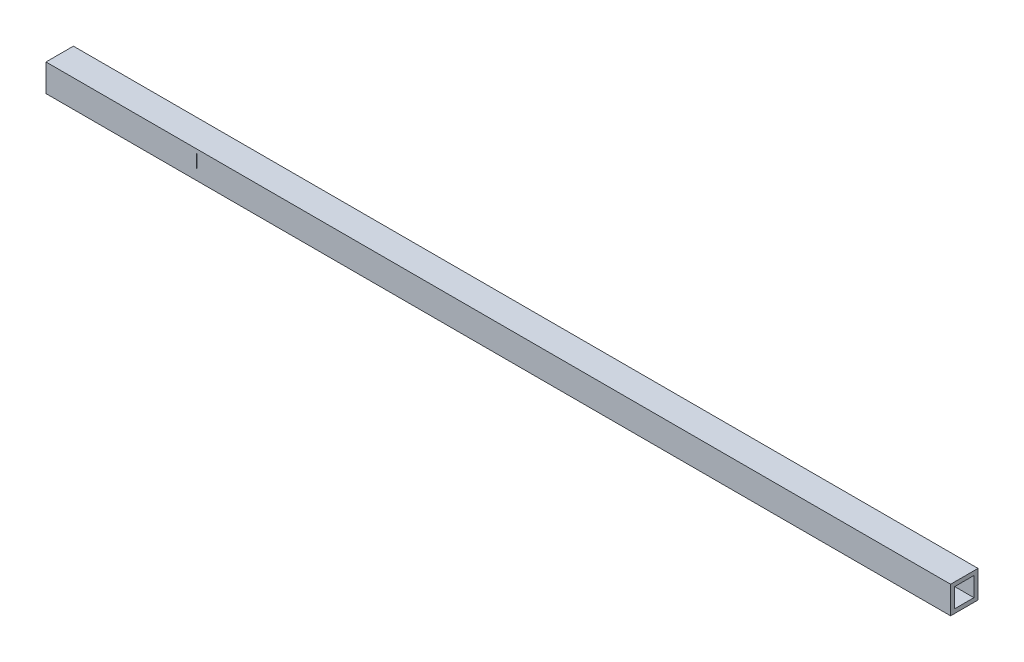
SolidWorks part; units mm, degrees
ref_plane "Alzado" through (0, 0, 0) normal (0, 0, 1) x (1, 0, 0)
ref_plane "Planta" through (0, 0, 0) normal (0, 1, 0) x (1, 0, 0)
ref_plane "Vista lateral" through (0, 0, 0) normal (1, 0, 0) x (0, 0, -1)
ref_plane "Plano1" through (0, -5, 0) normal (0, -1, 0) x (1, 0, 0)
sketch "Croquis1" plane through (0, -5, 0) normal (0, -1, 0) x (1, 0, 0)
  line L0 (0, 5) -> (0, -5)
  line L1 (0, -5) -> (330, -5)
  line L2 (330, -5) -> (330, 5)
  line L3 (330, 5) -> (0, 5)
  dimension "D1" = 330
extrude "Saliente-Extruir1" add sketch "Croquis1" against normal blind 10
sketch "Croquis2" plane through (0, 0, 0) normal (-1, 0, 0) x (0, 0, 1)
  line L0 (3.5, 3.5) -> (-3.5, 3.5)
  line L1 (-3.5, 3.5) -> (-3.5, -3.5)
  line L2 (-3.5, -3.5) -> (3.5, -3.5)
  line L3 (3.5, -3.5) -> (3.5, 3.5)
extrude "Cortar-Extruir1" cut sketch "Croquis2" against normal through all
sketch "Croquis3" plane through (0, 0, 5) normal (0, 0, 1) x (1, 0, 0)
  line L0 (25.01, -1.1667) -> (25.01, 3.5)
  line L1 (25.01, 3.5) -> (24.99, 3.5)
  line L2 (24.99, 3.5) -> (24.99, -1.1667)
  line L3 (24.99, -1.1667) -> (25.01, -1.1667)
extrude "Cortar-Extruir2" cut sketch "Croquis3" against normal blind 0.02
sketch "Croquis4" plane through (0, 0, 5) normal (0, 0, 1) x (1, 0, 0)
  line L0 (35.01, -1.1667) -> (35.01, 3.5)
  line L1 (35.01, 3.5) -> (34.99, 3.5)
  line L2 (34.99, 3.5) -> (34.99, -1.1667)
  line L3 (34.99, -1.1667) -> (35.01, -1.1667)
extrude "Cortar-Extruir3" cut sketch "Croquis4" against normal blind 0.02
sketch "Croquis5" plane through (0, 0, 5) normal (0, 0, 1) x (1, 0, 0)
  line L0 (45.01, -1.1667) -> (45.01, 3.5)
  line L1 (45.01, 3.5) -> (44.99, 3.5)
  line L2 (44.99, 3.5) -> (44.99, -1.1667)
  line L3 (44.99, -1.1667) -> (45.01, -1.1667)
extrude "Cortar-Extruir4" cut sketch "Croquis5" against normal blind 0.02
sketch "Croquis6" plane through (0, 0, 5) normal (0, 0, 1) x (1, 0, 0)
  line L0 (55.01, -1.1667) -> (55.01, 3.5)
  line L1 (55.01, 3.5) -> (54.99, 3.5)
  line L2 (54.99, 3.5) -> (54.99, -1.1667)
  line L3 (54.99, -1.1667) -> (55.01, -1.1667)
extrude "Cortar-Extruir5" cut sketch "Croquis6" against normal blind 0.02
sketch "Croquis7" plane through (0, 0, 5) normal (0, 0, 1) x (1, 0, 0)
  line L0 (65.01, -1.1667) -> (65.01, 3.5)
  line L1 (65.01, 3.5) -> (64.99, 3.5)
  line L2 (64.99, 3.5) -> (64.99, -1.1667)
  line L3 (64.99, -1.1667) -> (65.01, -1.1667)
extrude "Cortar-Extruir6" cut sketch "Croquis7" against normal blind 0.02
sketch "Croquis8" plane through (0, 0, 5) normal (0, 0, 1) x (1, 0, 0)
  line L0 (75.01, -1.1667) -> (75.01, 3.5)
  line L1 (75.01, 3.5) -> (74.99, 3.5)
  line L2 (74.99, 3.5) -> (74.99, -1.1667)
  line L3 (74.99, -1.1667) -> (75.01, -1.1667)
extrude "Cortar-Extruir7" cut sketch "Croquis8" against normal blind 0.02
sketch "Croquis9" plane through (0, 0, 5) normal (0, 0, 1) x (1, 0, 0)
  line L0 (85.01, -1.1667) -> (85.01, 3.5)
  line L1 (85.01, 3.5) -> (84.99, 3.5)
  line L2 (84.99, 3.5) -> (84.99, -1.1667)
  line L3 (84.99, -1.1667) -> (85.01, -1.1667)
extrude "Cortar-Extruir8" cut sketch "Croquis9" against normal blind 0.02
sketch "Croquis10" plane through (0, 0, 5) normal (0, 0, 1) x (1, 0, 0)
  line L0 (15.01, -1.1667) -> (15.01, 3.5)
  line L1 (15.01, 3.5) -> (14.99, 3.5)
  line L2 (14.99, 3.5) -> (14.99, -1.1667)
  line L3 (14.99, -1.1667) -> (15.01, -1.1667)
extrude "Cortar-Extruir9" cut sketch "Croquis10" against normal blind 0.02
